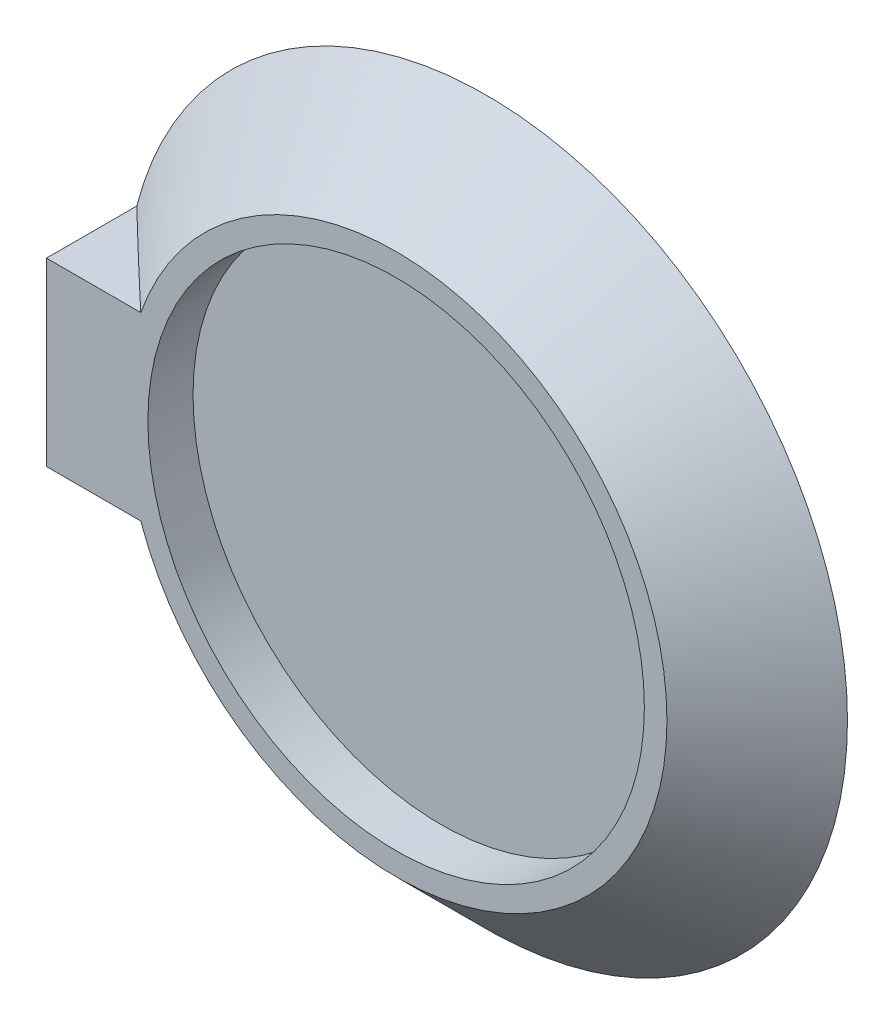
SolidWorks part; units mm, degrees
ref_plane "정면" through (0, 0, 0) normal (0, 0, 1) x (1, 0, 0)
ref_plane "윗면" through (0, 0, 0) normal (0, 1, 0) x (1, 0, 0)
ref_plane "우측면" through (0, 0, 0) normal (1, 0, 0) x (0, 0, -1)
sketch "스케치1" plane through (0, 0, 0) normal (0, 0, 1) x (1, 0, 0)
  circle A0 centre (0, 0) radius 60
  dimension "D1" = 120
extrude "보스-돌출1" add sketch "스케치1" against normal blind 20 draft 45 draft outward yes
sketch "스케치2" plane through (0, 0, 0) normal (0, 0, 1) x (1, 0, 0)
  circle A0 centre (0, 0) radius 55
  dimension "D1" = 110
extrude "컷-돌출1" cut sketch "스케치2" against normal blind 10
sketch "스케치3" plane through (0, 0, 0) normal (0, 0, 1) x (1, 0, 0)
  line L0 (-60, 20) -> (-56.5685, 20)
  line L1 (-60, -20) -> (-77.4597, -20)
  line L2 (-60, -20) -> (-60, 20)
  line L3 (-60, 20) -> (-77.4597, 20)
  line L4 (-77.4597, -20) -> (-77.4597, 20)
  line L5 (-60, -20) -> (-56.5685, -20)
  circle A0 centre (0, 0) radius 80 construction
  circle A1 centre (0, 0) radius 60 construction
  arc A2 (-56.5685, -20) -> (-56.5685, 20) centre (0, 0) cw
  dimension "D1" = 40
extrude "보스-돌출2" add sketch "스케치3" against normal blind 20 contours L4 L1 L2 L3 | L5 A2 L2 | L2 A2 L0
sketch "스케치4" plane through (-77.4597, 0, 0) normal (-1, 0, 0) x (0, 0, 1)
  line L0 (-20, 20) -> (-20, -20)
  arc A0 (-20, 20) -> (-20, -20) centre (-42.3607, 0) cw
  dimension "D1" = 30
extrude "컷-돌출2" cut sketch "스케치4" against normal blind 20 draft 45
